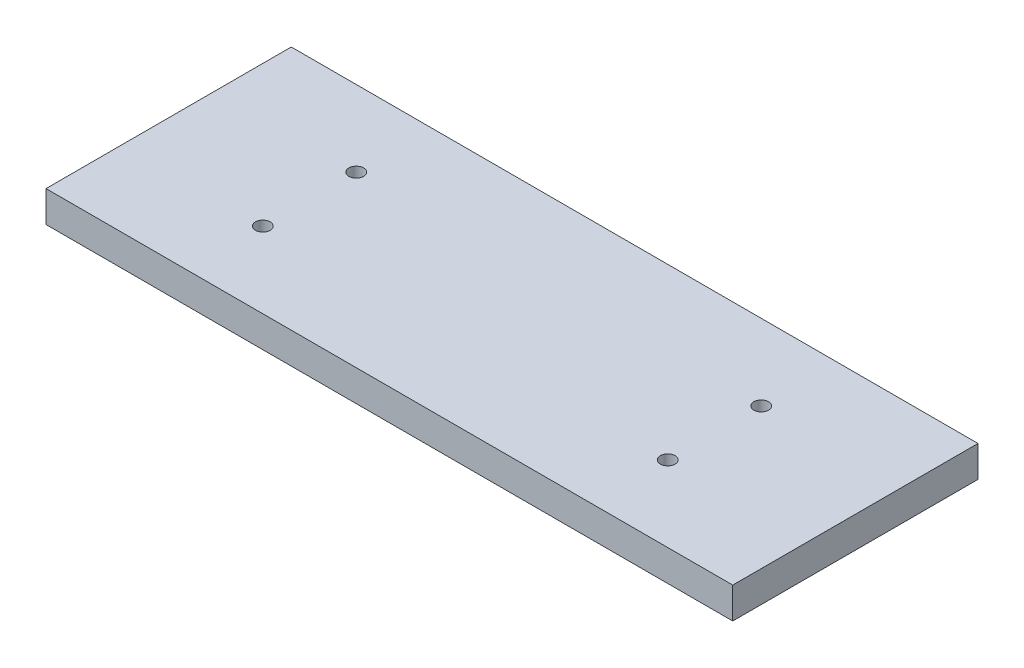
SolidWorks part; units mm, degrees
ref_plane "Front Plane" through (0, 0, 0) normal (0, 0, 1) x (1, 0, 0)
ref_plane "Top Plane" through (0, 0, 0) normal (0, 1, 0) x (1, 0, 0)
ref_plane "Right Plane" through (0, 0, 0) normal (1, 0, 0) x (0, 0, -1)
sketch "Sketch1" plane through (0, 0, 0) normal (0, 1, 0) x (1, 0, 0)
  line L1 (-63.8053, 18.1195) -> (76.1947, 18.1195)
  line L2 (-63.8053, 18.1195) -> (-63.8053, -31.8805)
  line L3 (-63.8053, -31.8805) -> (76.1947, -31.8805)
  line L4 (76.1947, 18.1195) -> (76.1947, -31.8805)
  dimension "D1" = 140
  dimension "D2" = 50
extrude "Boss-Extrude1" add sketch "Sketch1" along normal blind 6.35
sketch "Sketch2" plane through (0, 6.35, 0) normal (0, 1, 0) x (1, 0, 0)
  line L0 (76.1947, 18.1195) -> (-63.8053, 18.1195) construction
  line L1 (-63.8053, 18.1195) -> (-63.8053, -31.8805) construction
  circle A0 centre (-35.0803, 2.6445) radius 1.5
  circle A1 centre (-35.0803, -16.4055) radius 1.5
  circle A2 centre (47.4697, -16.4055) radius 1.5
  circle A3 centre (47.4697, 2.6445) radius 1.5
  dimension "D1" = 3
  dimension "D2" = 3
  dimension "D3" = 3
  dimension "D4" = 3
  dimension "D5" = 19.05
  dimension "D6" = 82.55
  dimension "D7" = 82.55
  dimension "D8" = 19.05
  dimension "D9" = 15.475
  dimension "D10" = 28.725
extrude "Cut-Extrude1" cut sketch "Sketch2" against normal blind 6.35
